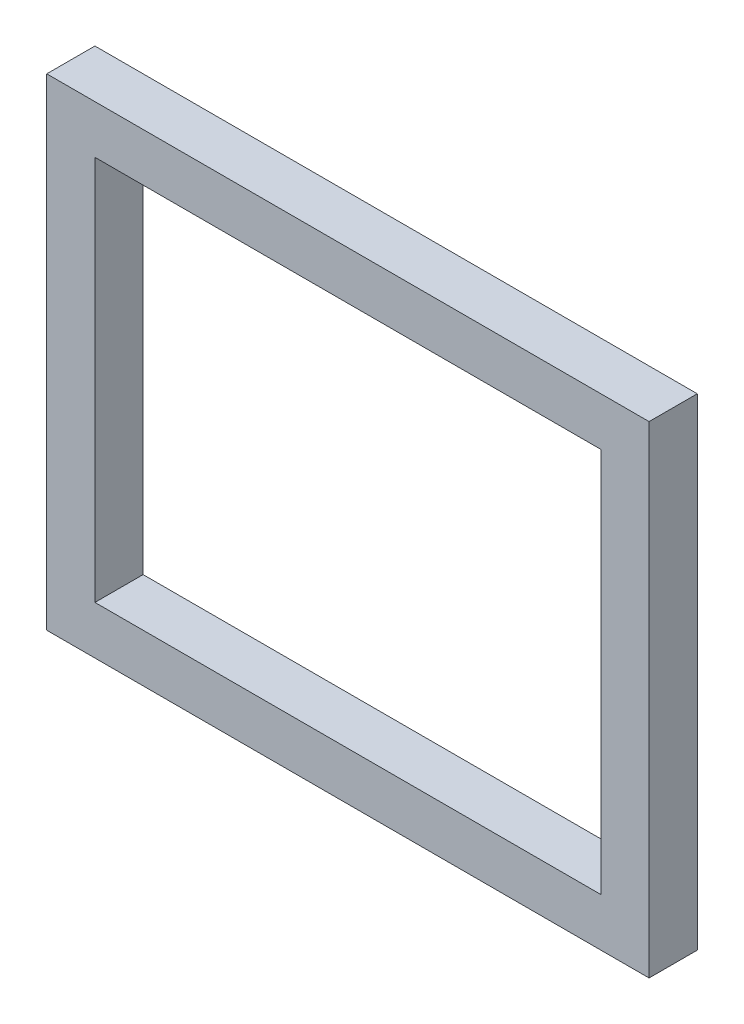
SolidWorks part; units mm, degrees
ref_plane "前视基准面" through (0, 0, 0) normal (0, 0, 1) x (1, 0, 0)
ref_plane "上视基准面" through (0, 0, 0) normal (0, 1, 0) x (1, 0, 0)
ref_plane "右视基准面" through (0, 0, 0) normal (1, 0, 0) x (0, 0, -1)
other "Configuration Table"
sketch "草图1" plane through (0, 0, 0) normal (0, 0, 1) x (1, 0, 0)
  line L0 (-125, 100) -> (125, 100)
  line L5 (-125, 100) -> (125, -100) construction
  line L6 (-125, -100) -> (125, 100) construction
  line L7 (125, -100) -> (-125, -100)
  line L8 (125, 100) -> (125, -100)
  line L9 (-125, 100) -> (-125, -100)
  point P0 (0, 0)
extrude "凸台-拉伸1" add sketch "草图1" along normal blind 20
sketch "草图2" plane through (0, 0, 20) normal (0, 0, 1) x (1, 0, 0)
  line L1 (-105, 80) -> (105, 80)
  line L2 (-105, 80) -> (-105, -80)
  line L3 (-105, -80) -> (105, -80)
  line L4 (105, 80) -> (105, -80)
  line L5 (-105, 80) -> (105, -80) construction
  line L6 (-105, -80) -> (105, 80) construction
  point P0 (0, 0)
extrude "切除-拉伸1" cut sketch "草图2" against normal blind 20
